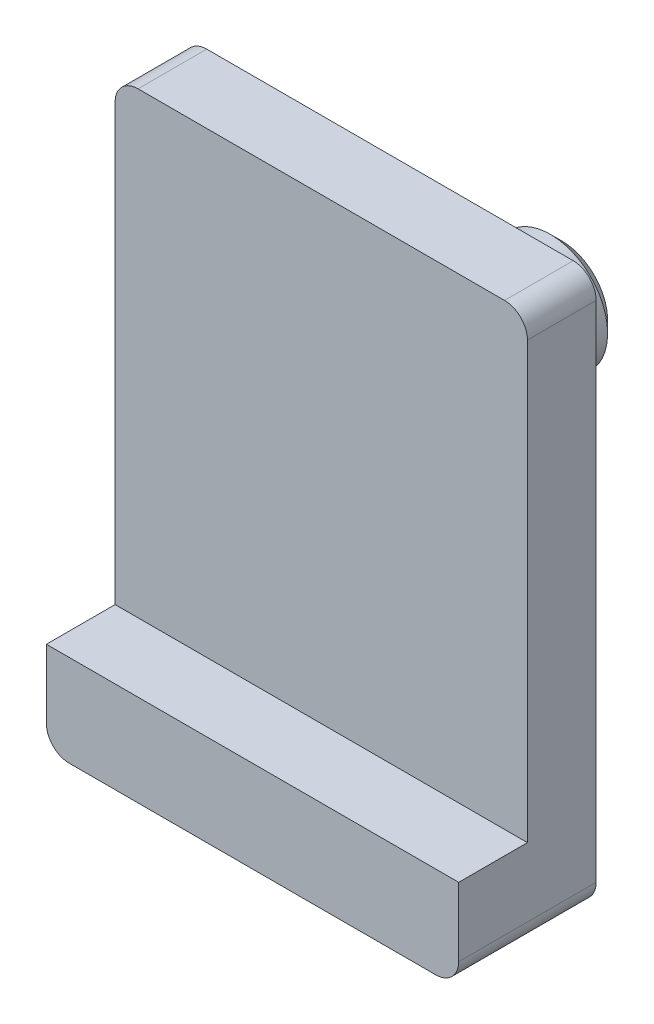
SolidWorks part; units mm, degrees
ref_plane "Front Plane" through (0, 0, 0) normal (0, 0, 1) x (1, 0, 0)
ref_plane "Top Plane" through (0, 0, 0) normal (0, 1, 0) x (1, 0, 0)
ref_plane "Right Plane" through (0, 0, 0) normal (1, 0, 0) x (0, 0, -1)
sketch "Sketch1" plane through (0, 0, 0) normal (0, 0, 1) x (1, 0, 0)
  line L1 (1, 0) -> (17, 0)
  line L2 (0, 1) -> (0, 23)
  line L3 (1, 24) -> (17, 24)
  line L4 (18, 1) -> (18, 23)
  arc A0 (1, 0) -> (0, 1) centre (1, 1) cw
  arc A1 (17, 0) -> (18, 1) centre (17, 1) ccw
  arc A2 (17, 24) -> (18, 23) centre (17, 23) cw
  arc A3 (0, 23) -> (1, 24) centre (1, 23) cw
  point P7 (0, 0)
  point P10 (18, 0)
  point P15 (0, 24)
  dimension "D3" = 1
  dimension "D1" = 18
  dimension "D2" = 24
extrude "Boss-Extrude1" add sketch "Sketch1" along normal blind 3
sketch "Sketch2" plane through (0, 0, 3) normal (0, 0, 1) x (1, 0, 0)
  line L0 (18, 1) -> (18, 23) construction
  line L1 (1, 0) -> (17, 0)
  line L2 (0, 1) -> (0, 4)
  line L3 (0, 4) -> (18, 4)
  line L4 (18, 1) -> (18, 4)
  arc A0 (17, 0) -> (18, 1) centre (17, 1) ccw
  arc A1 (1, 0) -> (0, 1) centre (1, 1) cw
  point P11 (0, 0)
  dimension "D2" = 1
  dimension "D1" = 4
extrude "Boss-Extrude2" add sketch "Sketch2" along normal blind 3
sketch "Sketch3" plane through (0, 0, 0) normal (0, 0, -1) x (-1, 0, 0)
  line L0 (-18, 1) -> (-18, 23) construction
  line L1 (-17, 24) -> (-1, 24) construction
  line L2 (-1, 0) -> (-17, 0) construction
  line L3 (0, 23) -> (0, 1) construction
  circle A0 centre (-15, 21) radius 2.5
  circle A1 centre (-3, 7) radius 2.5
  dimension "D1" = 5
  dimension "D2" = 3
  dimension "D3" = 3
  dimension "D4" = 7
  dimension "D5" = 3
extrude "Boss-Extrude3" add sketch "Sketch3" along normal blind 1.5
chamfer "Chamfer1" distance 0.5 angle 45 2 edges at (0.5, 7, -1.5) (12.5, 21, -1.5)
